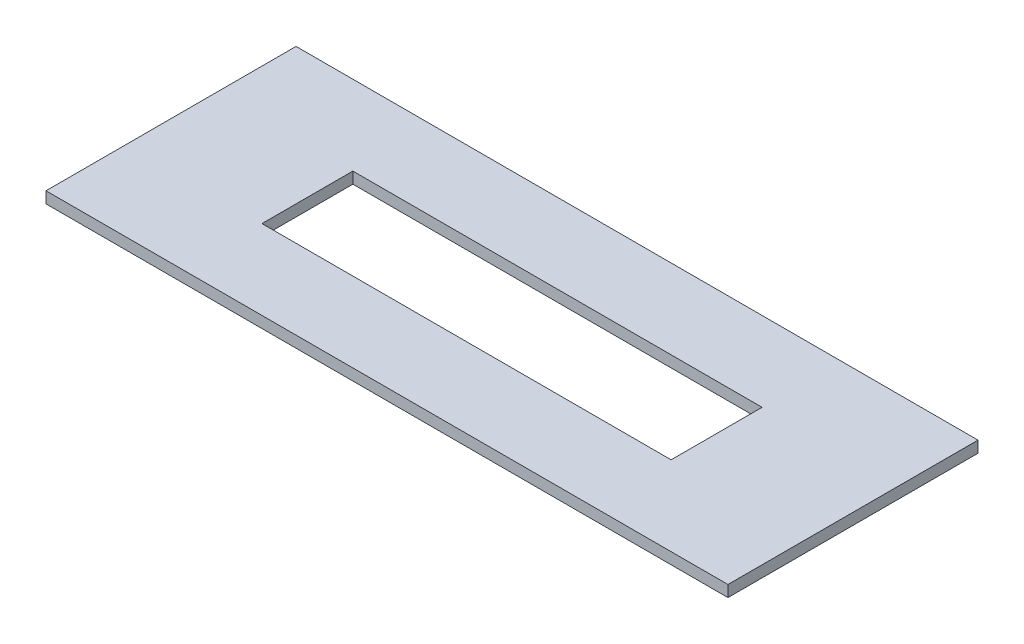
SolidWorks part; units mm, degrees
ref_plane "Front Plane" through (0, 0, 0) normal (0, 0, 1) x (1, 0, 0)
ref_plane "Top Plane" through (0, 0, 0) normal (0, 1, 0) x (1, 0, 0)
ref_plane "Right Plane" through (0, 0, 0) normal (1, 0, 0) x (0, 0, -1)
sketch "Sketch1" plane through (0, 0, 0) normal (0, 1, 0) x (1, 0, 0)
  line L1 (-23.8125, 8.7312) -> (23.8125, 8.7312)
  line L2 (-23.8125, 8.7312) -> (-23.8125, -8.7313)
  line L3 (-23.8125, -8.7313) -> (23.8125, -8.7313)
  line L4 (23.8125, 8.7312) -> (23.8125, -8.7313)
  line L5 (-23.8125, 8.7312) -> (23.8125, -8.7313) construction
  line L6 (-23.8125, -8.7313) -> (23.8125, 8.7312) construction
  line L7 (-14.2875, 3.175) -> (14.2875, 3.175)
  line L8 (-14.2875, 3.175) -> (-14.2875, -3.175)
  line L9 (-14.2875, -3.175) -> (14.2875, -3.175)
  line L10 (14.2875, 3.175) -> (14.2875, -3.175)
  line L11 (-14.2875, 3.175) -> (14.2875, -3.175) construction
  line L12 (-14.2875, -3.175) -> (14.2875, 3.175) construction
  point P0 (0, 0)
  point P6 (0, 0)
  dimension "D1" = 47.625
  dimension "D2" = 17.4625
  dimension "D3" = 6.35
  dimension "D4" = 28.575
extrude "Boss-Extrude1" add sketch "Sketch1" along normal blind 0.7937
